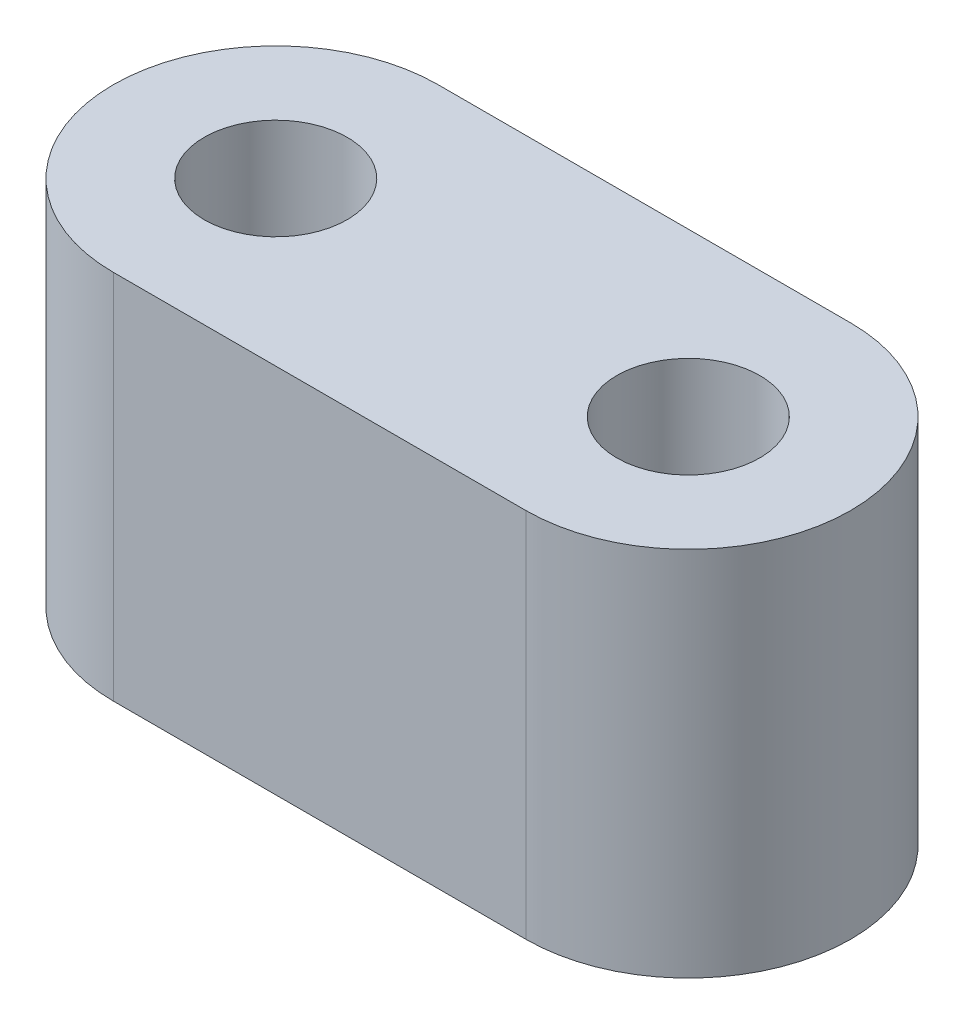
SolidWorks part; units mm, degrees
ref_plane "Front Plane" through (0, 0, 0) normal (0, 0, 1) x (1, 0, 0)
ref_plane "Top Plane" through (0, 0, 0) normal (0, 1, 0) x (1, 0, 0)
ref_plane "Right Plane" through (0, 0, 0) normal (1, 0, 0) x (0, 0, -1)
sketch "Sketch1" plane through (0, 0, 0) normal (0, 1, 0) x (1, 0, 0)
  line L0 (0, 0) -> (12.7, 0) construction
  line L1 (0, 5) -> (12.7, 5)
  line L2 (0, -5) -> (12.7, -5)
  circle A0 centre (0, 0) radius 2.2
  circle A1 centre (12.7, 0) radius 2.2
  arc A2 (0, 5) -> (0, -5) centre (0, 0) ccw
  arc A3 (12.7, -5) -> (12.7, 5) centre (12.7, 0) ccw
  point P5 (6.35, 0)
  dimension "D1" = 4.4
  dimension "D2" = 12.7
  dimension "D3" = 10
extrude "Boss-Extrude1" add sketch "Sketch1" along normal blind 11.43
